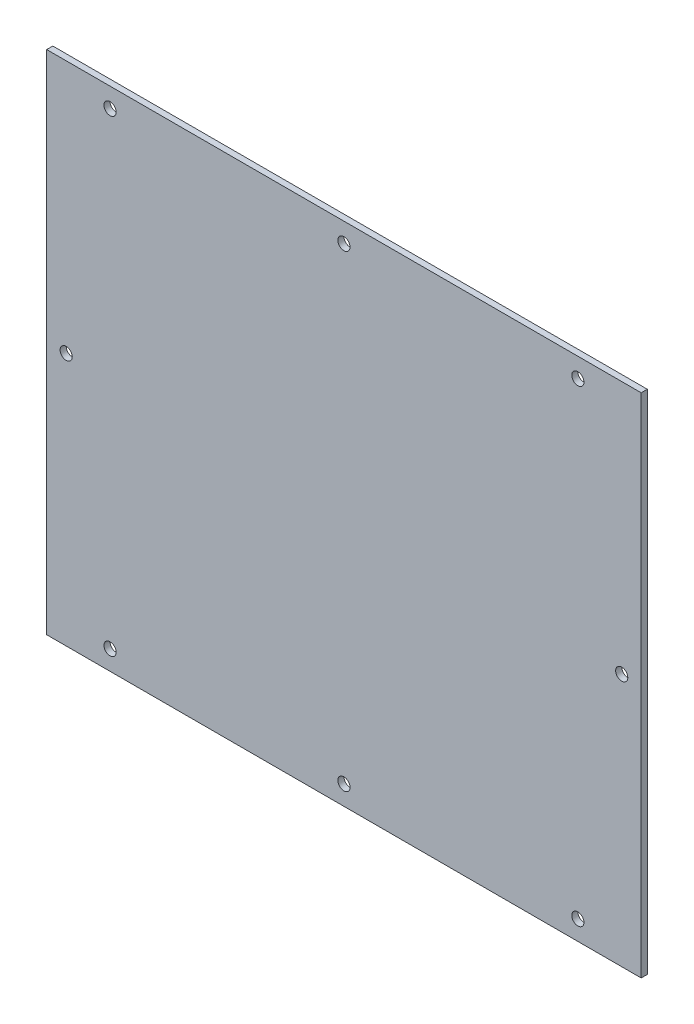
SolidWorks part; units mm, degrees
ref_plane "Front Plane" through (0, 0, 0) normal (0, 0, 1) x (1, 0, 0)
ref_plane "Top Plane" through (0, 0, 0) normal (0, 1, 0) x (1, 0, 0)
ref_plane "Right Plane" through (0, 0, 0) normal (1, 0, 0) x (0, 0, -1)
sketch "Sketch1" plane through (0, 0, 0) normal (0, 0, 1) x (1, 0, 0)
  line L0 (-193.675, 0) -> (-180.975, 0) construction
  line L1 (-193.675, -165.1) -> (193.675, -165.1)
  line L2 (-193.675, -165.1) -> (-193.675, 165.1)
  line L3 (-193.675, 165.1) -> (193.675, 165.1)
  line L4 (193.675, -165.1) -> (193.675, 165.1)
  line L5 (-193.675, -165.1) -> (193.675, 165.1) construction
  line L6 (-193.675, 165.1) -> (193.675, -165.1) construction
  line L7 (0, 165.1) -> (0, 152.4) construction
  line L8 (0, -55) -> (0, 55) construction
  line L9 (55, 0) -> (-55, 0) construction
  circle A0 centre (-180.975, 0) radius 3.9687
  circle A1 centre (0, 152.4) radius 3.9687
  circle A2 centre (152.4, 152.4) radius 3.9687
  circle A3 centre (-152.4, 152.4) radius 3.9687
  circle A4 centre (180.975, 0) radius 3.9687
  circle A5 centre (152.4, -152.4) radius 3.9687
  circle A6 centre (0, -152.4) radius 3.9687
  circle A7 centre (-152.4, -152.4) radius 3.9687
  point P0 (0, 0)
  dimension "D4" = 7.9375
  dimension "D6" = 7.9375
  dimension "D1" = 330.2
  dimension "D2" = 387.35
  dimension "D3" = 12.7
  dimension "D5" = 12.7
  dimension "D7" = 2
  dimension "D8" = 2
extrude "Boss-Extrude1" add sketch "Sketch1" along normal blind 3.9878
